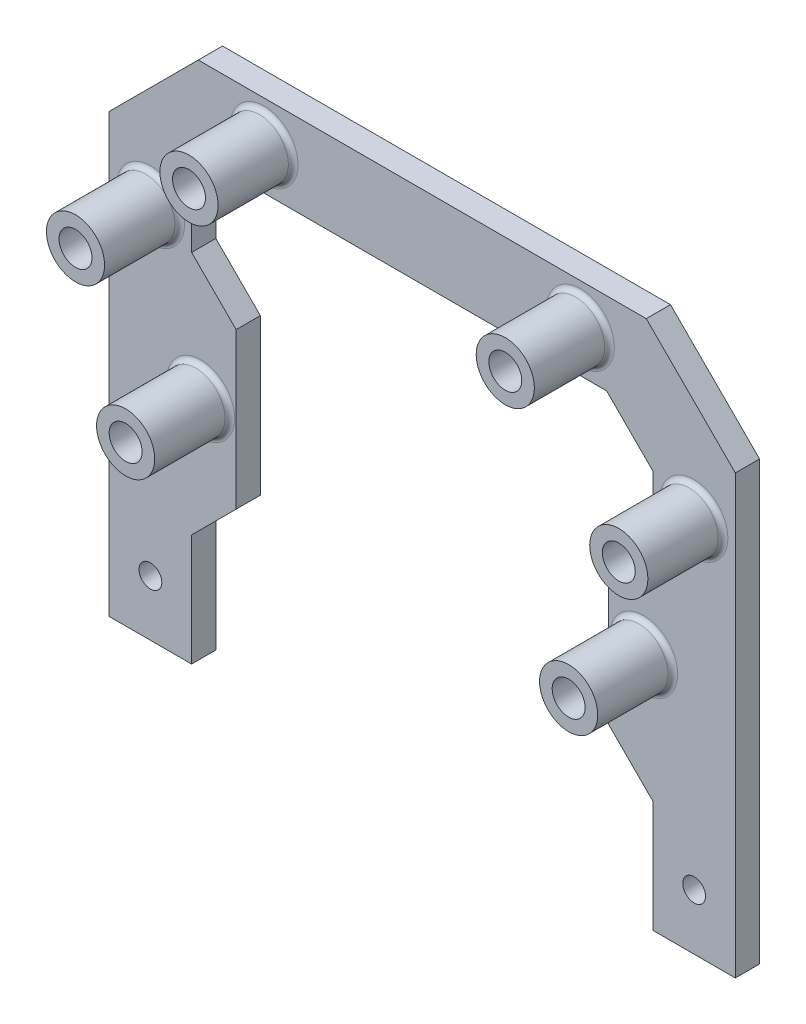
SolidWorks part; units mm, degrees
ref_plane "Front Plane" through (0, 0, 0) normal (0, 0, 1) x (1, 0, 0)
ref_plane "Top Plane" through (0, 0, 0) normal (0, 1, 0) x (1, 0, 0)
ref_plane "Right Plane" through (0, 0, 0) normal (1, 0, 0) x (0, 0, -1)
sketch "Sketch2" plane through (0, 0, 0) normal (0, 0, 1) x (1, 0, 0)
  line L0 (-64.5954, 0) -> (64.5954, 0) construction
  line L2 (-36.0554, 88.6243) -> (36.0554, 88.6243) construction
  line L3 (-38.6151, 31.7729) -> (-47.1004, 23.2876) construction
  line L4 (-47.1004, 73.3367) -> (-38.6151, 64.8514) construction
  line L6 (0, 0) -> (0, 120.7475) construction
  line L8 (-38.0349, 91.6243) -> (0, 91.6243)
  line L9 (-46.2156, 108.6243) -> (0, 108.6243)
  line L14 (46.2156, 108.6243) -> (0, 108.6243)
  line L15 (38.0349, 91.6243) -> (0, 91.6243)
  line L16 (-57.3534, 54.5983) -> (-42.8577, 69.094) construction
  line L21 (-42.8577, 27.5303) -> (-57.3534, 42.026) construction
  line L22 (42.8577, 27.5303) -> (57.3534, 42.026) construction
  line L23 (-46.2156, 108.6243) -> (-64.5954, 90.2445)
  line L24 (-47.5954, 73.5488) -> (-47.5954, 82.0638)
  line L25 (-38.0349, 91.6243) -> (-47.5954, 82.0638)
  line L26 (-64.5954, 0) -> (-47.5954, 0)
  line L27 (-38.403, 64.3564) -> (-38.403, 32.2679)
  line L28 (-47.5954, 23.0755) -> (-38.403, 32.2679)
  line L29 (-38.403, 64.3564) -> (-47.5954, 73.5488)
  line L30 (-47.5954, 23.0755) -> (-47.5954, 0)
  line L31 (-64.5954, 0) -> (-64.5954, 90.2445)
  line L32 (42.7586, 68.9949) -> (57.3534, 54.5983) construction
  line L33 (64.5954, 0) -> (64.5954, 90.2445)
  line L34 (47.5954, 23.0755) -> (47.5954, 0)
  line L35 (38.403, 64.3564) -> (47.5954, 73.5488)
  line L36 (47.5954, 23.0755) -> (38.403, 32.2679)
  line L37 (38.403, 64.3564) -> (38.403, 32.2679)
  line L38 (64.5954, 0) -> (47.5954, 0)
  line L39 (38.0349, 91.6243) -> (47.5954, 82.0638)
  line L40 (47.5954, 73.5488) -> (47.5954, 82.0638)
  line L41 (46.2156, 108.6243) -> (64.5954, 90.2445)
  line L42 (-53.1108, 46.2686) -> (-61.5961, 37.7833) construction
  line L43 (-61.5961, 58.841) -> (-53.1108, 50.3557) construction
  point P34 (0, 0)
  point P38 (0, 108.6243)
  point P39 (0, 91.6243)
  point P40 (-42.9992, 27.6717)
  dimension "D2" = 17
  dimension "D4" = 13
  dimension "D3" = 0.2
  dimension "D5" = 17
  dimension "D6" = 45
  dimension "D7" = 13
  dimension "D8" = 3
  dimension "D10" = 0.2
extrude "Boss-Extrude2" add sketch "Sketch2" against normal blind 5
sketch "Sketch4" plane through (0, 0, 0) normal (0, 0, 1) x (1, 0, 0)
  line L0 (56.0954, 0) -> (55.4055, 99.4344) construction
  line L1 (55.4055, 99.4344) -> (-55.4055, 99.4344) construction
  line L2 (-55.4055, 99.4344) -> (-56.0954, 0) construction
  line L3 (-38.403, 48.3122) -> (-64.4972, 48.3122) construction
  line L4 (38.403, 48.3122) -> (64.4972, 48.3122) construction
  line L5 (38.403, 64.3564) -> (38.403, 32.2679) construction
  line L8 (-46.2156, 108.6243) -> (-64.5954, 90.2445) construction
  line L9 (64.5954, 90.2445) -> (46.2156, 108.6243) construction
  line L10 (-38.403, 32.2679) -> (-38.403, 64.3564) construction
  line L11 (42.9992, 27.6717) -> (42.9992, 68.9526) construction
  line L12 (47.5954, 73.5488) -> (38.403, 64.3564) construction
  line L13 (38.403, 32.2679) -> (47.5954, 23.0755) construction
  line L14 (47.5954, 77.8063) -> (64.4972, 77.8063) construction
  line L15 (47.5954, 82.0638) -> (47.5954, 73.5488) construction
  line L16 (31.2176, 108.8703) -> (31.2176, 91.6243) construction
  line L17 (0, 108.6243) -> (0, 91.6243) construction
  line L19 (47.5954, 0) -> (64.5954, 0) construction
  circle A0 centre (45.703, 48.3122) radius 6
  circle A1 centre (56.0463, 77.8063) radius 6
  circle A2 centre (32.6276, 100.1896) radius 6
  circle A3 centre (-32.6276, 100.1896) radius 6
  circle A4 centre (-45.703, 48.3122) radius 6
  circle A5 centre (-56.0463, 77.8063) radius 6
  point P11 (56.0463, 77.8063)
  point P12 (-55.7504, 49.7172)
  dimension "D1" = 12
  dimension "D3" = 7.3
  dimension "D2" = 12
  dimension "D5" = 12
  dimension "D4" = 15
extrude "Boss-Extrude3" add sketch "Sketch4" along normal blind 15.5
fillet "Fillet1" radius 1 6 edges at (26.6276, 100.1896, 0) (50.0463, 77.8063, 0) (39.703, 48.3122, 0) (-51.703, 48.3122, 0) (-62.0463, 77.8063, 0) (-38.6276, 100.1896, 0)
sketch "Sketch5" plane through (0, 0, -5) normal (0, 0, -1) x (-1, 0, 0)
  circle A0 centre (56.0954, 11.5) radius 2.35 construction
  circle A1 centre (-56.0954, 11.5) radius 2.35 construction
  circle A2 centre (56.0954, 11.5) radius 2.35
  circle A3 centre (-56.0954, 11.5) radius 2.35
extrude "Cut-Extrude1" cut sketch "Sketch5" against normal up to surface (8.2 mm away)
sketch "Sketch6" plane through (0, 0, 15.5) normal (0, 0, 1) x (1, 0, 0)
  circle A0 centre (-45.703, 48.3122) radius 6 construction
  circle A1 centre (-45.703, 48.3122) radius 6 construction
  circle A2 centre (45.703, 48.3122) radius 6 construction
  circle A3 centre (56.0463, 77.8063) radius 6 construction
  circle A4 centre (32.6276, 100.1896) radius 6 construction
  circle A5 centre (-32.6276, 100.1896) radius 6 construction
  circle A6 centre (-56.0463, 77.8063) radius 6 construction
  circle A7 centre (45.703, 48.3122) radius 6 construction
  circle A8 centre (56.0463, 77.8063) radius 6 construction
  circle A9 centre (32.6276, 100.1896) radius 6 construction
  circle A10 centre (-32.6276, 100.1896) radius 6 construction
  circle A11 centre (-56.0463, 77.8063) radius 6 construction
  circle A12 centre (-56.0463, 77.8063) radius 3.4
  circle A13 centre (-32.6276, 100.1896) radius 3.4
  circle A14 centre (32.6276, 100.1896) radius 3.4
  circle A15 centre (56.0463, 77.8063) radius 3.4
  circle A16 centre (45.703, 48.3122) radius 3.4
  circle A17 centre (-45.703, 48.3122) radius 3.4
  dimension "D1" = 6.8
extrude "Cut-Extrude2" cut sketch "Sketch6" against normal blind 10
